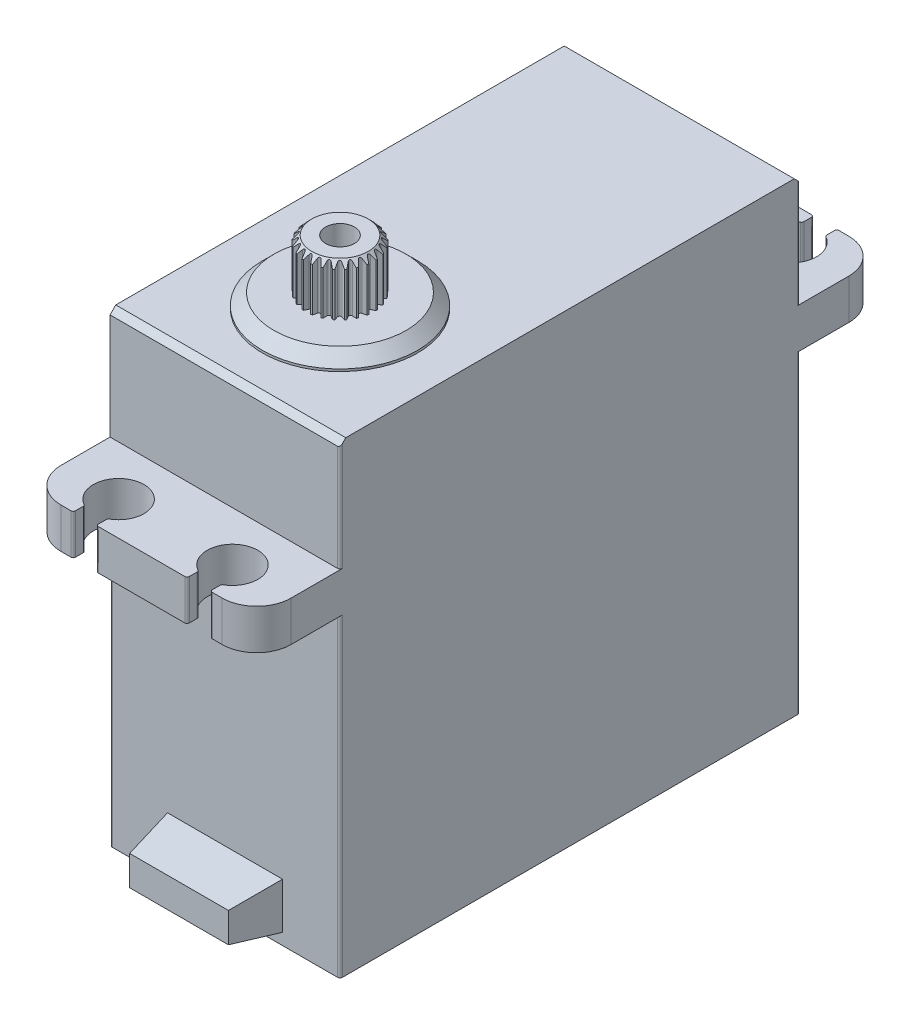
SolidWorks part; units mm, degrees
ref_plane "Front Plane" through (0, 0, 0) normal (0, 0, 1) x (1, 0, 0)
ref_plane "Top Plane" through (0, 0, 0) normal (0, 1, 0) x (1, 0, 0)
ref_plane "Right Plane" through (0, 0, 0) normal (1, 0, 0) x (0, 0, -1)
sketch "Sketch1" plane through (0, 0, 0) normal (1, 0, 0) x (0, 0, -1)
  line L0 (-1582.4765, 66.1077) -> (-1182.9248, 66.1077) construction
  line L1 (0.0812, 7.9132) -> (40.0812, 7.9132) construction
  line L2 (0, 0) -> (40, 0)
  line L3 (40, 0) -> (40, 27.3)
  line L4 (40, 27.3) -> (47.25, 27.3)
  line L5 (47.25, 27.3) -> (47.25, 30.8)
  line L6 (47.25, 30.8) -> (40, 30.8)
  line L7 (40, 30.8) -> (40, 40)
  line L10 (0.5, 40.5) -> (0, 40)
  line L11 (0, 40) -> (0, 30.8)
  line L12 (0, 30.8) -> (-7.25, 30.8)
  line L13 (-7.25, 30.8) -> (-7.25, 27.3)
  line L14 (-7.25, 27.3) -> (0, 27.3)
  line L15 (0, 27.3) -> (0, 0)
  line L16 (39.5, 40.5) -> (0.5, 40.5)
  line L17 (40, 40) -> (39.5, 40.5)
  dimension "D1" = 40
  dimension "D2" = 3.5
  dimension "D3" = 27.3
  dimension "D4" = 40
  dimension "D5" = 7.25
  dimension "D6" = 135
  dimension "D7" = 135
  dimension "D8" = 40.5
  dimension "D9" = 0.5
extrude "Boss-Extrude1" add sketch "Sketch1" along normal blind 20
sketch "Sketch2" plane through (0, 40.5, 0) normal (0, 1, 0) x (1, 0, 0)
  line L0 (10, 0.5) -> (10, 10) construction
  line L1 (20, 0.5) -> (0, 0.5) construction
  line L2 (20, 0) -> (0, 0) construction
  circle A0 centre (10, 10) radius 6.75
  dimension "D1" = 13.5
  dimension "D2" = 10
extrude "Boss-Extrude2" add sketch "Sketch2" along normal blind 1.2
chamfer "Chamfer1" distance 1 angle 45 1 edges at (10, 41.7, -3.25)
fillet "Fillet1" radius 3 4 edges at (0, 29.05, 7.25) (20, 29.05, 7.25) (0, 29.05, -47.25) (20, 29.05, -47.25)
sketch "Sketch3" plane through (0, 41.7, 0) normal (0, 1, 0) x (1, 0, 0)
  circle A0 centre (10, 10) radius 2.95
  dimension "D1" = 5.9
extrude "Boss-Extrude3" add sketch "Sketch3" along normal blind 46 from surface at -41.7 starting at face at (10, 0, -20)
chamfer "Chamfer2" distance 0.5 angle 45 1 edges at (10, 46, -7.05)
sketch "Sketch4" plane through (0, 46, 0) normal (0, 1, 0) x (1, 0, 0)
  line L0 (10, 12.95) -> (10.1351, 12.6216)
  line L1 (10.3981, 12.5947) -> (10.5969, 12.889)
  circle A0 centre (10, 10) radius 2.95 construction
  circle A1 centre (10, 10) radius 2.95 construction
  arc A2 (10.1351, 12.6216) -> (10.3981, 12.5947) centre (10.2738, 12.6787) ccw
  circle A3 centre (10, 10) radius 2.95
  circle M5 centre (10, 10) radius 2.45
  dimension "D1" = 0.6
  dimension "D2" = 0.15
extrude "Cut-Extrude1" cut sketch "Sketch4" against normal up to surface (4.3 mm away) contours L1 A3 L0 M5
pattern_circular "CirPattern3" count 25 over 360 about axis through (10, 0, -10) along (0, 1, 0) of "Cut-Extrude1"
sketch "Sketch5" plane through (0, 46, 0) normal (0, 1, 0) x (1, 0, 0)
  point P0 (10, 10)
hole_wizard "M3x0.5 Tapped Hole1" positions "Sketch6" profile "Sketch8" tap size "M3x0.5" standard "ANSI Metric"
sketch "Sketch6" plane through (0, 46, 0) normal (0, 1, 0) x (1, 0, 0)
  point P0 (10, 10)
sketch "Sketch8" plane through (10, 46, -10) normal (1, 0, 0) x (0, 0, 1)
  line L0 (0, 0) -> (0, 4.7511)
  line L1 (0, 4.7511) -> (1.25, 4)
  line L2 (1.25, 4) -> (1.25, 0)
  line L5 (1.25, 0) -> (0, 0)
  line L10 (0, 4.7511) -> (-1.25, 4) construction
  line L11 (0, -6.35) -> (0, 107.95) construction
  dimension "Tap Drill Dia." = 2.5
  dimension "Tap Drill Depth" = 4
  dimension "Drill Angle" = 118
cosmetic thread "Hole Thread1" parameters "D1"=6, "D2"=3
sketch "Sketch9" plane through (0, 30.8, 0) normal (0, 1, 0) x (1, 0, 0)
  line L0 (0, 20) -> (31.2709, 20) construction
  line L1 (0, 0) -> (0, 40) construction
  line L2 (5.05, -4.3) -> (14.95, -4.3) construction
  line L3 (17, -7.25) -> (3, -7.25) construction
  line L4 (15.95, 46.2596) -> (15.95, 49.0358)
  line L5 (4.05, -6.2596) -> (6.05, -6.2596)
  line L6 (4.05, -6.2596) -> (4.05, -9.0358)
  line L7 (4.05, -9.0358) -> (6.05, -9.0358)
  line L8 (6.05, -6.2596) -> (6.05, -9.0358)
  line L9 (13.95, -6.2596) -> (15.95, -6.2596)
  line L10 (13.95, -6.2596) -> (13.95, -9.0358)
  line L11 (13.95, -9.0358) -> (15.95, -9.0358)
  line L12 (15.95, -6.2596) -> (15.95, -9.0358)
  line L13 (13.95, 49.0358) -> (15.95, 49.0358)
  line L14 (13.95, 46.2596) -> (13.95, 49.0358)
  line L15 (13.95, 46.2596) -> (15.95, 46.2596)
  line L16 (6.05, 46.2596) -> (6.05, 49.0358)
  line L17 (4.05, 49.0358) -> (6.05, 49.0358)
  line L18 (4.05, 46.2596) -> (4.05, 49.0358)
  line L19 (4.05, 46.2596) -> (6.05, 46.2596)
  circle A0 centre (5.05, -4.3) radius 2.2
  circle A1 centre (14.95, -4.3) radius 2.2
  circle A2 centre (14.95, 44.3) radius 2.2
  circle A3 centre (5.05, 44.3) radius 2.2
  point P8 (10, -4.3)
  point P9 (10, -7.25)
  point P37 (10, 47.25)
  point P38 (10, 44.3)
  line M11 (3, -7.25) -> (17, -7.25)
  dimension "D1" = 9.9
  dimension "D2" = 4.4
  dimension "D3" = 2
  dimension "D4" = 24.3
extrude "Cut-Extrude2" cut sketch "Sketch9" against normal blind 46 contours L9 A1 | L9 A1 | A1 L10 L12 M11 | L12 L10 L11 M11 | L5 A0 | L5 A0 | A0 L6 L8 M11 | L8 L6 L7 M11 | A2 L15 | A2 L15 | L14 A2 L4 L13 | A3 L19 | L18 A3 L16 L17 | A3 L19
fillet "Fillet2" radius 0.2 23 edges at (13.95, 29.05, -47.25) (6.05, 29.05, -47.25) (6.05, 29.05, -46.2596) (4.05, 29.05, -46.2596) (15.95, 29.05, -47.25) (15.95, 29.05, -46.2596) (13.95, 29.05, -46.2596) (4.05, 29.05, -47.25) (0, 13.65, -40) (0, 35.4, -40) (20, 35.4, 0) (20, 35.4, -40) (20, 13.65, -40) (6.05, 29.05, 7.25) (13.95, 29.05, 7.25) (13.95, 29.05, 6.2596) (15.95, 29.05, 6.2596) (15.95, 29.05, 7.25) (20, 13.65, 0) (0, 13.65, 0) (4.05, 29.05, 6.2596) (6.05, 29.05, 6.2596) (4.05, 29.05, 7.25)
sketch "Sketch10" plane through (0, 0, 0) normal (0, 0, 1) x (1, 0, 0)
  line L0 (19.8, 0) -> (0.2, 0) construction
  line L1 (15, 1) -> (5, 1)
  line L2 (15, 1) -> (15, 5)
  line L3 (15, 5) -> (5, 5)
  line L4 (5, 1) -> (5, 5)
  line L5 (15, 1) -> (5, 5) construction
  line L6 (15, 5) -> (5, 1) construction
  point P0 (10, 3)
  point P8 (10, 0)
  dimension "D1" = 10
  dimension "D2" = 4
  dimension "D3" = 1
extrude "Boss-Extrude4" add sketch "Sketch10" along normal blind 4 draft 10
sketch "Sketch13" plane through (20, 0, 0) normal (1, 0, 0) x (0, 0, -1)
  line L0 (20, 40.5) -> (20, 0) construction
  line L1 (39.5, 40.5) -> (0.5, 40.5) construction
  line L2 (0.2, 0) -> (39.8, 0) construction
  line L3 (39.8, 30.8) -> (20, 30.8) construction
sketch "Sketch19" plane through (0, 40.5, 0) normal (0, 1, 0) x (1, 0, 0)
  line L0 (5.05, 44.3) -> (5.05, 40) construction
  line L1 (19.8, 40) -> (0.2, 40) construction
  line L2 (10, 47.25) -> (10, 40) construction
  line L3 (13.75, 47.25) -> (6.25, 47.25) construction
  circle A0 centre (5.05, 44.3) radius 2.2
